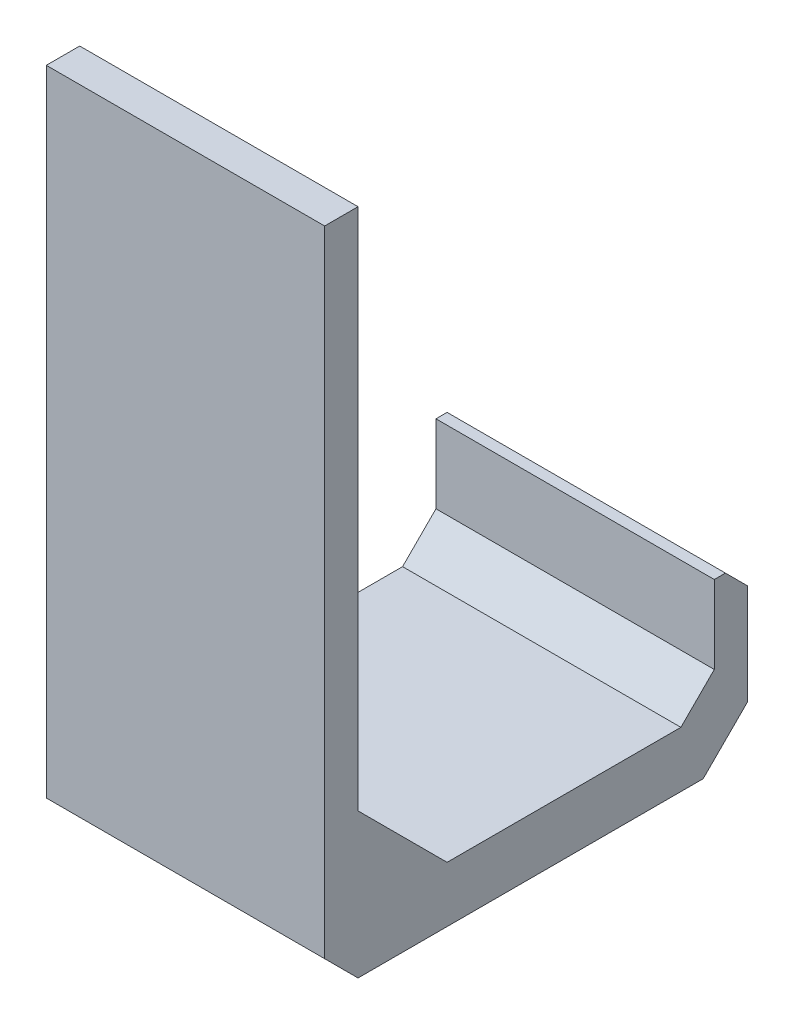
SolidWorks part; units mm, degrees
ref_plane "Front Plane" through (0, 0, 0) normal (0, 0, 1) x (1, 0, 0)
ref_plane "Top Plane" through (0, 0, 0) normal (0, 1, 0) x (1, 0, 0)
ref_plane "Right Plane" through (0, 0, 0) normal (1, 0, 0) x (0, 0, -1)
sketch "Sketch1" plane through (0, 0, 0) normal (1, 0, 0) x (0, 0, -1)
  line L1 (-10.2273, 11.0227) -> (-7.2273, 11.0227)
  line L2 (-10.2273, 11.0227) -> (-10.2273, -48.9773)
  line L3 (-10.2273, -48.9773) -> (-7.2273, -48.9773)
  line L4 (-7.2273, 11.0227) -> (-7.2273, -43.9773)
  line L5 (-7.2273, -48.9773) -> (27.7727, -48.9773)
  line L7 (-7.2273, -43.9773) -> (24.7727, -43.9773)
  line L8 (27.7727, -48.9773) -> (27.7727, -43.9773)
  line L10 (27.7727, -43.9773) -> (27.7727, -33.9773)
  line L11 (27.7727, -33.9773) -> (24.7727, -33.9773)
  line L12 (24.7727, -43.9773) -> (24.7727, -33.9773)
  dimension "D1" = 5
  dimension "D2" = 3
  dimension "D3" = 3
  dimension "D4" = 60
  dimension "D5" = 35
  dimension "D6" = 10
extrude "Boss-Extrude1" add sketch "Sketch1" along normal blind 25
chamfer "Chamfer1" distance 8 angle 45 1 edges at (12.5, -43.9773, 7.2273)
chamfer "Chamfer2" distance 3 angle 45 2 edges at (12.5, -48.9773, 10.2273) (12.5, -43.9773, -24.7727)
chamfer "Chamfer3" distance 4 angle 45 1 edges at (12.5, -48.9773, -27.7727)
chamfer "Chamfer4" distance 2 angle 45 1 edges at (12.5, -33.9773, -27.7727)
